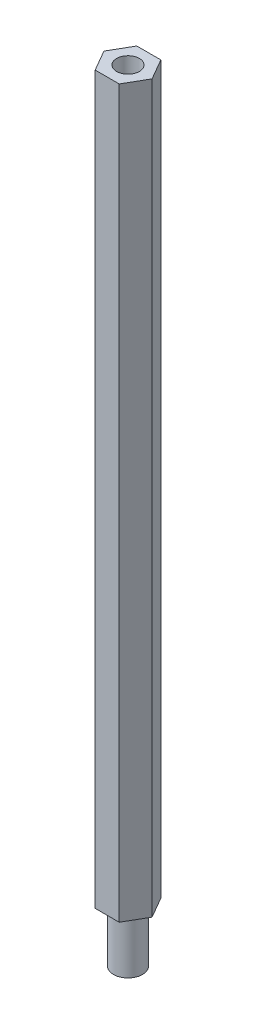
SolidWorks part; units mm, degrees
ref_plane "前视基准面" through (0, 0, 0) normal (0, 0, 1) x (1, 0, 0)
ref_plane "上视基准面" through (0, 0, 0) normal (0, 1, 0) x (1, 0, 0)
ref_plane "右视基准面" through (0, 0, 0) normal (1, 0, 0) x (0, 0, -1)
sketch "草图4" plane through (0, 0, 0) normal (0, 1, 0) x (1, 0, 0)
  line L0 (-12.7945, 0) -> (16.3015, 0) construction
  line L2 (1.325, -2.295) -> (2.65, 0)
  line L3 (2.65, 0) -> (1.325, 2.295)
  line L4 (1.325, 2.295) -> (-1.325, 2.295)
  line L5 (-1.325, 2.295) -> (-2.65, 0)
  line L6 (-2.65, 0) -> (-1.325, -2.295)
  line L7 (-1.325, -2.295) -> (1.325, -2.295)
  circle A0 centre (0, 0) radius 2.295 construction
  dimension "D1" = 5.3
extrude "凸台-拉伸1" add sketch "草图4" along normal blind 80
sketch "草图6" plane through (0, 0, 0) normal (0, -1, 0) x (-1, 0, 0)
  circle A0 centre (0, 0) radius 1.6
  dimension "D1" = 3.2
extrude "凸台-拉伸2" add sketch "草图6" along normal blind 6
cosmetic thread "装饰螺纹线1"
sketch "草图7" plane through (0, 80, 0) normal (0, 1, 0) x (1, 0, 0)
  circle A0 centre (0, 0) radius 1.25
  dimension "D1" = 2.5
extrude "切除-拉伸1" cut sketch "草图7" against normal blind 5
cosmetic thread "装饰螺纹线2" parameters "D2"=3
